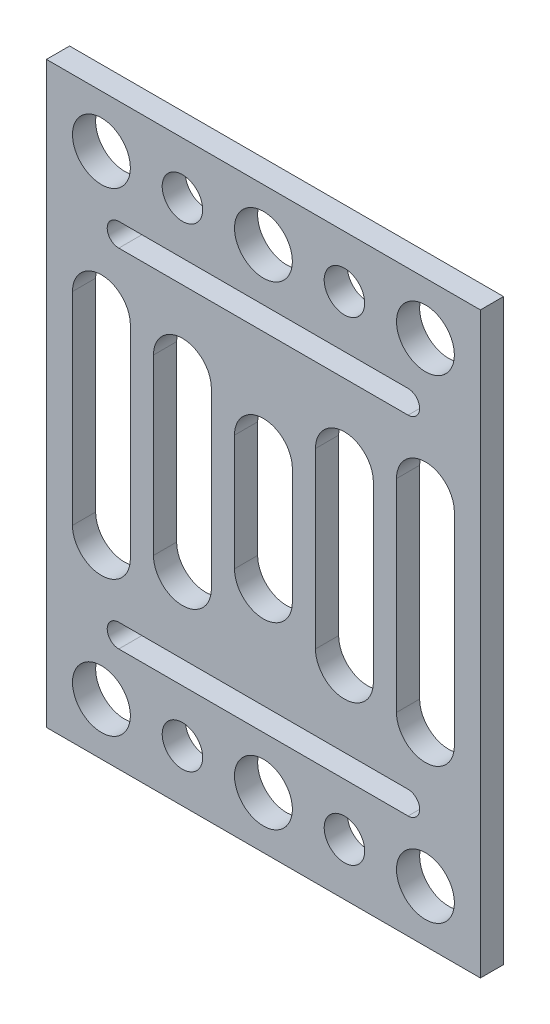
SolidWorks part; units mm, degrees
ref_plane "Ebene vorne" through (0, 0, 0) normal (0, 0, 1) x (1, 0, 0)
ref_plane "Ebene oben" through (0, 0, 0) normal (0, 1, 0) x (1, 0, 0)
ref_plane "Ebene rechts" through (0, 0, 0) normal (1, 0, 0) x (0, 0, -1)
sketch "Skizze1" plane through (0, 0, 0) normal (0, 0, 1) x (1, 0, 0)
  line L0 (-37.5, 0) -> (0, 0) construction
  line L1 (37.5, 50) -> (-37.5, 50)
  line L2 (37.5, 50) -> (37.5, -50)
  line L3 (37.5, -50) -> (-37.5, -50)
  line L4 (-37.5, 50) -> (-37.5, -50)
  line L5 (37.5, 50) -> (-37.5, -50) construction
  line L6 (37.5, -50) -> (-37.5, 50) construction
  line L7 (0, 0) -> (0, 30) construction
  line L8 (25, 30) -> (-25, 30) construction
  line L9 (25, 28) -> (-25, 28)
  line L10 (25, 32) -> (-25, 32)
  line L11 (25, -30) -> (-25, -30) construction
  line L12 (25, -28) -> (-25, -28)
  line L13 (25, -32) -> (-25, -32)
  arc A0 (25, 28) -> (25, 32) centre (25, 30) ccw
  arc A1 (-25, 32) -> (-25, 28) centre (-25, 30) ccw
  arc A2 (25, -28) -> (25, -32) centre (25, -30) cw
  arc A3 (-25, -32) -> (-25, -28) centre (-25, -30) cw
  point P0 (0, 0)
  point P11 (0, 30)
  point P18 (0, -30)
  dimension "D3" = 2
  dimension "D1" = 75
  dimension "D2" = 100
  dimension "D4" = 50
  dimension "D5" = 60
extrude "Grundplatte" add sketch "Skizze1" along normal blind 4
sketch "Skizze2" plane through (0, 0, 4) normal (0, 0, 1) x (1, 0, 0)
  line L0 (-28, -17.5) -> (-28, 17.5) construction
  line L1 (-33, -17.5) -> (-33, 17.5)
  line L2 (-23, -17.5) -> (-23, 17.5)
  line L3 (0, 10) -> (0, -10) construction
  line L4 (5, 10) -> (5, -10)
  line L5 (-5, 10) -> (-5, -10)
  line L6 (-14, 15) -> (-14, -15) construction
  line L7 (-9, 15) -> (-9, -15)
  line L8 (-19, 15) -> (-19, -15)
  line L9 (-28, 0) -> (-14, 0) construction
  line L10 (-14, 0) -> (0, 0) construction
  line L11 (0, 0) -> (0, -32) construction
  line L12 (-25, -32) -> (25, -32) construction
  line L13 (28, 0) -> (14, 0) construction
  line L14 (14, 15) -> (14, -15) construction
  line L15 (9, 15) -> (9, -15)
  line L16 (19, 15) -> (19, -15)
  line L17 (28, -17.5) -> (28, 17.5) construction
  line L18 (33, -17.5) -> (33, 17.5)
  line L19 (23, -17.5) -> (23, 17.5)
  line L20 (-28, 41) -> (-14, 41) construction
  line L21 (-14, 41) -> (0, 41) construction
  line L22 (0, 41) -> (14, 41) construction
  line L23 (14, 41) -> (28, 41) construction
  line L24 (0, 50) -> (0, 41) construction
  line L25 (37.5, 50) -> (-37.5, 50) construction
  line L26 (0, 41) -> (0, 32) construction
  line L27 (25, 32) -> (-25, 32) construction
  line L28 (0, -41) -> (0, -32) construction
  line L29 (0, -50) -> (0, -41) construction
  line L30 (14, -41) -> (28, -41) construction
  line L31 (0, -41) -> (14, -41) construction
  line L32 (-14, -41) -> (0, -41) construction
  line L33 (-28, -41) -> (-14, -41) construction
  arc A0 (-33, -17.5) -> (-23, -17.5) centre (-28, -17.5) ccw
  arc A1 (-23, 17.5) -> (-33, 17.5) centre (-28, 17.5) ccw
  arc A2 (5, 10) -> (-5, 10) centre (0, 10) ccw
  arc A3 (-5, -10) -> (5, -10) centre (0, -10) ccw
  arc A4 (-9, 15) -> (-19, 15) centre (-14, 15) ccw
  arc A5 (-19, -15) -> (-9, -15) centre (-14, -15) ccw
  arc A6 (9, 15) -> (19, 15) centre (14, 15) cw
  arc A7 (19, -15) -> (9, -15) centre (14, -15) cw
  arc A8 (33, -17.5) -> (23, -17.5) centre (28, -17.5) cw
  arc A9 (23, 17.5) -> (33, 17.5) centre (28, 17.5) cw
  circle A10 centre (-28, 41) radius 5
  circle A11 centre (0, 41) radius 5
  circle A12 centre (28, 41) radius 5
  circle A13 centre (-14, 41) radius 3.5
  circle A14 centre (14, 41) radius 3.5
  circle A15 centre (14, -41) radius 3.5
  circle A16 centre (-14, -41) radius 3.5
  circle A17 centre (28, -41) radius 5
  circle A18 centre (0, -41) radius 5
  circle A19 centre (-28, -41) radius 5
  point P2 (-28, 0)
  point P8 (0, 0)
  point P16 (-14, 0)
  point P32 (14, 0)
  point P39 (28, 0)
  dimension "D2" = 5
  dimension "D6" = 10
  dimension "D7" = 7
  dimension "D1" = 14
  dimension "D3" = 35
  dimension "D4" = 30
  dimension "D5" = 20
extrude "Schnitt-Linear austragen1" cut sketch "Skizze2" against normal through all
